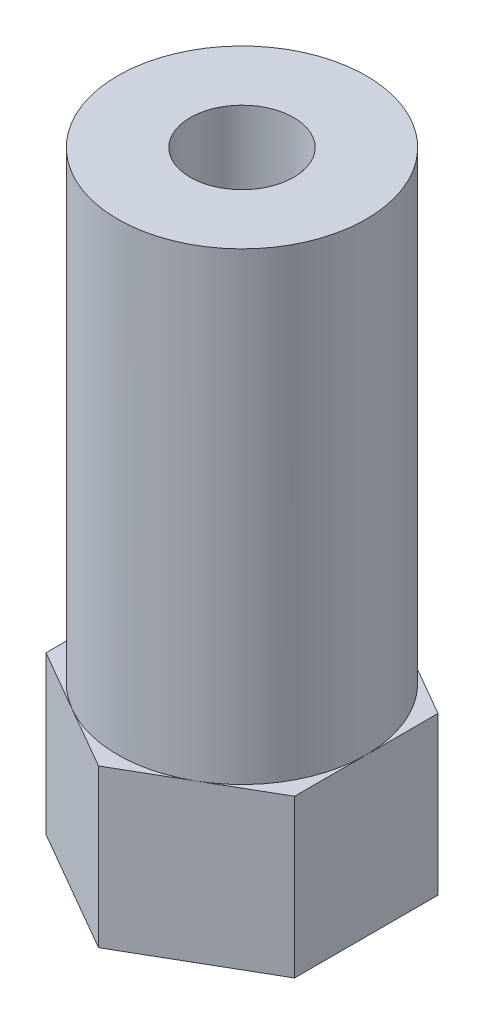
SolidWorks part; units mm, degrees
material "Brass"
ref_plane "Front Plane" through (0, 0, 0) normal (0, 0, 1) x (1, 0, 0)
ref_plane "Top Plane" through (0, 0, 0) normal (0, 1, 0) x (1, 0, 0)
ref_plane "Right Plane" through (0, 0, 0) normal (1, 0, 0) x (0, 0, -1)
sketch "Sketch1" plane through (0, 0, 0) normal (0, 1, 0) x (1, 0, 0)
  line L1 (0, -6.9282) -> (6, -3.4641)
  line L2 (6, -3.4641) -> (6, 3.4641)
  line L3 (6, 3.4641) -> (0, 6.9282)
  line L4 (0, 6.9282) -> (-6, 3.4641)
  line L5 (-6, 3.4641) -> (-6, -3.4641)
  line L6 (-6, -3.4641) -> (0, -6.9282)
  circle A0 centre (0, 0) radius 6 construction
  dimension "D1" = 12
  dimension "D2" = 6
extrude "Boss-Extrude1" add sketch "Sketch1" along normal blind 7.6
sketch "Sketch2" plane through (0, 7.6, 0) normal (0, 1, 0) x (1, 0, 0)
  circle A0 centre (0, 0) radius 6
extrude "Boss-Extrude2" add sketch "Sketch2" along normal blind 22.4
sketch "Sketch3" plane through (0, 30, 0) normal (0, 1, 0) x (1, 0, 0)
  circle A0 centre (0, 0) radius 2.5
  dimension "D1" = 5
extrude "Cut-Extrude1" cut sketch "Sketch3" against normal through all
sketch3d "3DSketch1" plane through (0, 0, 0) normal (0, 0, 1) x (1, 0, 0)
  dimension "D1" = 10
sketch "Sketch4" plane through (8, 0, -13.8564) normal (0.5, 0, -0.866) x (-0.866, 0, -0.5)
  line L0 (0, 31.5674) -> (0, -1.7665) construction
  line L1 (2.5, 30) -> (-2.5, 30) construction
  circle A0 centre (0, 27.46) radius 1
  dimension "D1" = 2
  dimension "D2" = 2.54
extrude "Cut-Extrude2" cut sketch "Sketch4" against normal blind 15.4
